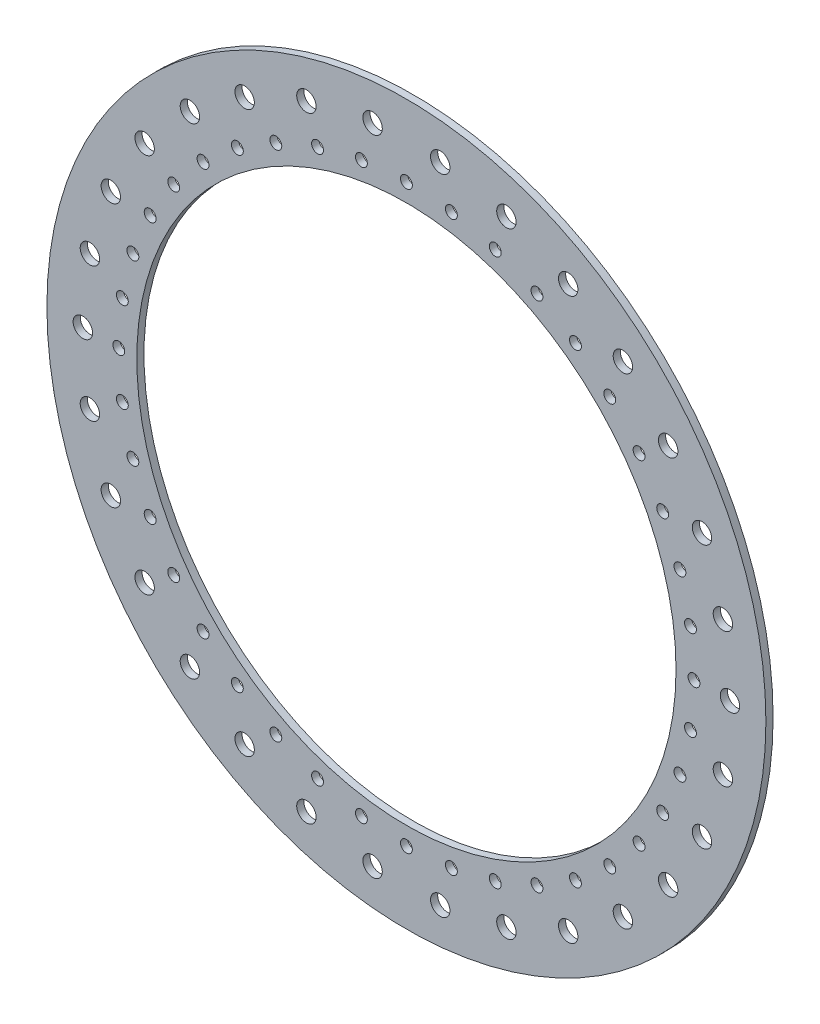
SolidWorks part; units mm, degrees
ref_plane "Alzado" through (0, 0, 0) normal (0, 0, 1) x (1, 0, 0)
ref_plane "Planta" through (0, 0, 0) normal (0, 1, 0) x (1, 0, 0)
ref_plane "Vista lateral" through (0, 0, 0) normal (1, 0, 0) x (0, 0, -1)
sketch "Croquis1" plane through (0, 0, 0) normal (0, 0, 1) x (1, 0, 0)
  circle A0 centre (0, 0) radius 200
  circle A1 centre (0, 0) radius 150
  circle A3 centre (145.6231, 105.8013) radius 5.4
  circle A4 centre (164.4382, 73.2126) radius 5.4
  circle A5 centre (176.0666, 37.4241) radius 5.4
  circle A6 centre (180, 0) radius 5.4
  circle A7 centre (176.0666, -37.4241) radius 5.4
  circle A8 centre (164.4382, -73.2126) radius 5.4
  circle A9 centre (145.6231, -105.8013) radius 5.4
  circle A10 centre (120.4435, -133.7661) radius 5.4
  circle A11 centre (90, -155.8846) radius 5.4
  circle A12 centre (55.6231, -171.1902) radius 5.4
  circle A13 centre (18.8151, -179.0139) radius 5.4
  circle A14 centre (-18.8151, -179.0139) radius 5.4
  circle A15 centre (-55.6231, -171.1902) radius 5.4
  circle A16 centre (-90, -155.8846) radius 5.4
  circle A17 centre (-120.4435, -133.7661) radius 5.4
  circle A18 centre (-145.6231, -105.8013) radius 5.4
  circle A19 centre (-164.4382, -73.2126) radius 5.4
  circle A20 centre (-176.0666, -37.4241) radius 5.4
  circle A21 centre (-180, 0) radius 5.4
  circle A22 centre (-176.0666, 37.4241) radius 5.4
  circle A23 centre (-164.4382, 73.2126) radius 5.4
  circle A24 centre (-145.6231, 105.8013) radius 5.4
  circle A25 centre (-120.4435, 133.7661) radius 5.4
  circle A26 centre (-90, 155.8846) radius 5.4
  circle A27 centre (-55.6231, 171.1902) radius 5.4
  circle A28 centre (-18.8151, 179.0139) radius 5.4
  circle A29 centre (18.8151, 179.0139) radius 5.4
  circle A30 centre (55.6231, 171.1902) radius 5.4
  circle A31 centre (90, 155.8846) radius 5.4
  circle A32 centre (120.4435, 133.7661) radius 5.4
extrude "Saliente-Extruir1" add sketch "Croquis1" along normal blind 4
sketch "Croquis3" plane through (0, 0, 0) normal (0, 0, -1) x (-1, 0, 0)
  line L1 (160, 0) -> (158.0301, 25.0295)
  line L2 (158.0301, 25.0295) -> (152.169, 49.4427)
  line L3 (152.169, 49.4427) -> (142.561, 72.6385)
  line L4 (142.561, 72.6385) -> (129.4427, 94.0456)
  line L5 (129.4427, 94.0456) -> (113.1371, 113.1371)
  line L6 (113.1371, 113.1371) -> (94.0456, 129.4427)
  line L7 (94.0456, 129.4427) -> (72.6385, 142.561)
  line L8 (72.6385, 142.561) -> (49.4427, 152.169)
  line L9 (49.4427, 152.169) -> (25.0295, 158.0301)
  line L10 (25.0295, 158.0301) -> (0, 160)
  line L11 (0, 160) -> (-25.0295, 158.0301)
  line L12 (-25.0295, 158.0301) -> (-49.4427, 152.169)
  line L13 (-49.4427, 152.169) -> (-72.6385, 142.561)
  line L14 (-72.6385, 142.561) -> (-94.0456, 129.4427)
  line L15 (-94.0456, 129.4427) -> (-113.1371, 113.1371)
  line L16 (-113.1371, 113.1371) -> (-129.4427, 94.0456)
  line L17 (-129.4427, 94.0456) -> (-142.561, 72.6385)
  line L18 (-142.561, 72.6385) -> (-152.169, 49.4427)
  line L19 (-152.169, 49.4427) -> (-158.0301, 25.0295)
  line L20 (-158.0301, 25.0295) -> (-160, 0)
  line L21 (-160, 0) -> (-158.0301, -25.0295)
  line L22 (-158.0301, -25.0295) -> (-152.169, -49.4427)
  line L23 (-152.169, -49.4427) -> (-142.561, -72.6385)
  line L24 (-142.561, -72.6385) -> (-129.4427, -94.0456)
  line L25 (-129.4427, -94.0456) -> (-113.1371, -113.1371)
  line L26 (-113.1371, -113.1371) -> (-94.0456, -129.4427)
  line L27 (-94.0456, -129.4427) -> (-72.6385, -142.561)
  line L28 (-72.6385, -142.561) -> (-49.4427, -152.169)
  line L29 (-49.4427, -152.169) -> (-25.0295, -158.0301)
  line L30 (-25.0295, -158.0301) -> (0, -160)
  line L31 (0, -160) -> (25.0295, -158.0301)
  line L32 (25.0295, -158.0301) -> (49.4427, -152.169)
  line L33 (49.4427, -152.169) -> (72.6385, -142.561)
  line L34 (72.6385, -142.561) -> (94.0456, -129.4427)
  line L35 (94.0456, -129.4427) -> (113.1371, -113.1371)
  line L36 (113.1371, -113.1371) -> (129.4427, -94.0456)
  line L37 (129.4427, -94.0456) -> (142.561, -72.6385)
  line L38 (142.561, -72.6385) -> (152.169, -49.4427)
  line L39 (152.169, -49.4427) -> (158.0301, -25.0295)
  line L40 (158.0301, -25.0295) -> (160, 0)
  circle A1 centre (0, 0) radius 159.5068 construction
hole_wizard "Taladro de margen para M61" positions "Croquis3D2" profile "Croquis5" hole size "M6" standard "Ansi Metric" end condition through all
sketch3d "Croquis3D2"
  point P0 (-113.1371, 113.1371, 0)
  point P3 (-94.0456, 129.4427, 0)
  point P6 (-72.6385, 142.561, 0)
  point P9 (-49.4427, 152.169, 0)
  point P12 (-129.4427, 94.0456, 0)
  point P15 (-142.561, 72.6385, 0)
  point P19 (-152.169, 49.4427, 0)
  point P22 (-158.0301, 25.0295, 0)
  point P25 (-160, 0, 0)
  point P28 (-158.0301, -25.0295, 0)
  point P31 (-152.169, -49.4427, 0)
  point P34 (-142.561, -72.6385, 0)
  point P37 (-129.4427, -94.0456, 0)
  point P40 (-113.1371, -113.1371, 0)
  point P43 (-94.0456, -129.4427, 0)
  point P46 (-72.6385, -142.561, 0)
  point P49 (-49.4427, -152.169, 0)
  point P52 (-25.0295, -158.0301, 0)
  point P55 (0, -160, 0)
  point P58 (25.0295, -158.0301, 0)
  point P61 (49.4427, -152.169, 0)
  point P64 (72.6385, -142.561, 0)
  point P67 (94.0456, -129.4427, 0)
  point P70 (113.1371, -113.1371, 0)
  point P73 (129.4427, -94.0456, 0)
  point P76 (142.561, -72.6385, 0)
  point P79 (152.169, -49.4427, 0)
  point P82 (158.0301, -25.0295, 0)
  point P85 (160, 0, 0)
  point P88 (158.0301, 25.0295, 0)
  point P91 (152.169, 49.4427, 0)
  point P94 (142.561, 72.6385, 0)
  point P97 (129.4427, 94.0456, 0)
  point P100 (113.1371, 113.1371, 0)
  point P103 (94.0456, 129.4427, 0)
  point P106 (72.6385, 142.561, 0)
  point P109 (49.4427, 152.169, 0)
  point P112 (25.0295, 158.0301, 0)
  point P115 (0, 160, 0)
  point P118 (-25.0295, 158.0301, 0)
sketch "Croquis5" plane through (-113.1371, 113.1371, 0) normal (1, 0, 0) x (0, 1, 0)
  line L0 (0, 0) -> (0, 4)
  line L1 (0, 4) -> (3.3, 4)
  line L2 (3.3, 4) -> (3.3, 0)
  line L5 (3.3, 0) -> (0, 0)
  line L11 (0, -6.35) -> (0, 107.95) construction
  dimension "Diámetro de taladro hasta el siguiente" = 6.6
  dimension "Profundidad de taladro hasta el siguiente" = 4
